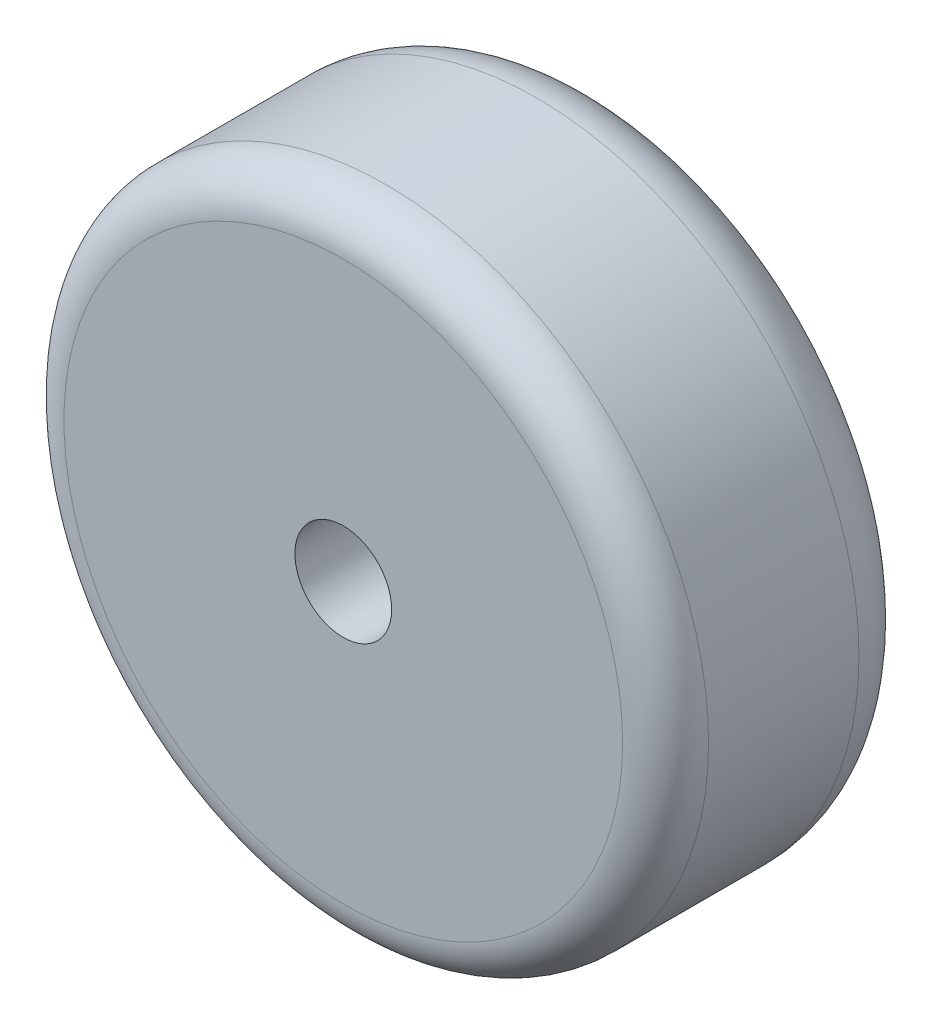
SolidWorks part; units mm, degrees
ref_plane "Спереди" through (0, 0, 0) normal (0, 0, 1) x (1, 0, 0)
ref_plane "Сверху" through (0, 0, 0) normal (0, 1, 0) x (1, 0, 0)
ref_plane "Справа" through (0, 0, 0) normal (1, 0, 0) x (0, 0, -1)
sketch "Эскиз1" plane through (0, 0, 0) normal (0, 0, 1) x (1, 0, 0)
  circle A0 centre (0, 0) radius 2.25
  circle A1 centre (0, 0) radius 15
  dimension "D1" = 4.5
  dimension "D2" = 30
extrude "Бобышка-Вытянуть1" add sketch "Эскиз1" along normal blind 12
sketch "Эскиз2" plane through (0, 0, 12) normal (0, 0, 1) x (1, 0, 0)
  circle A0 centre (0, 0) radius 4.65
  dimension "D1" = 9.3
extrude "Вырез-Вытянуть1" [suppressed] cut sketch "Эскиз2" against normal blind 4
fillet "Скругление1" radius 2 1 edges at (15, 0, 12)
fillet "Скругление2" radius 3 1 edges at (15, 0, 0)
